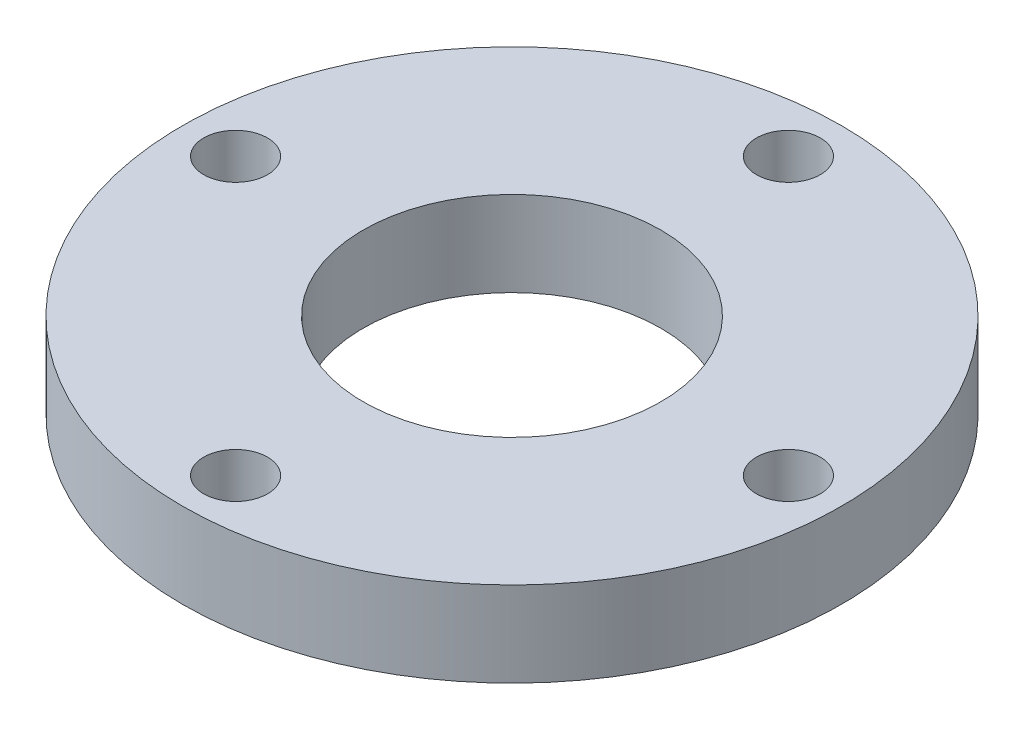
SolidWorks part; units mm, degrees
ref_plane "Front Plane" through (0, 0, 0) normal (0, 0, 1) x (1, 0, 0)
ref_plane "Top Plane" through (0, 0, 0) normal (0, 1, 0) x (1, 0, 0)
ref_plane "Right Plane" through (0, 0, 0) normal (1, 0, 0) x (0, 0, -1)
sketch "Sketch1" plane through (0, 0, 0) normal (0, 1, 0) x (1, 0, 0)
  circle A0 centre (0, 0) radius 15.5
  dimension "D1" = 31
extrude "Boss-Extrude1" add sketch "Sketch1" along normal blind 4
sketch "Sketch2" plane through (0, 0, 0) normal (0, -1, 0) x (1, 0, 0)
  circle A0 centre (0, 0) radius 7
  dimension "D1" = 14
extrude "center hole" cut sketch "Sketch2" against normal through all
sketch "Sketch3" plane through (0, 0, 0) normal (0, -1, 0) x (1, 0, 0)
  line L0 (0, 0) -> (0, 13) construction
  circle A0 centre (0, 13) radius 1.5
  dimension "D1" = 3
  dimension "D2" = 13
extrude "M2.5 hole" cut sketch "Sketch3" against normal through all
pattern_circular "CirPattern1" count 4 over 360 about axis through (0, 0, 0) along (0, 1, 0) of "M2.5 hole"
